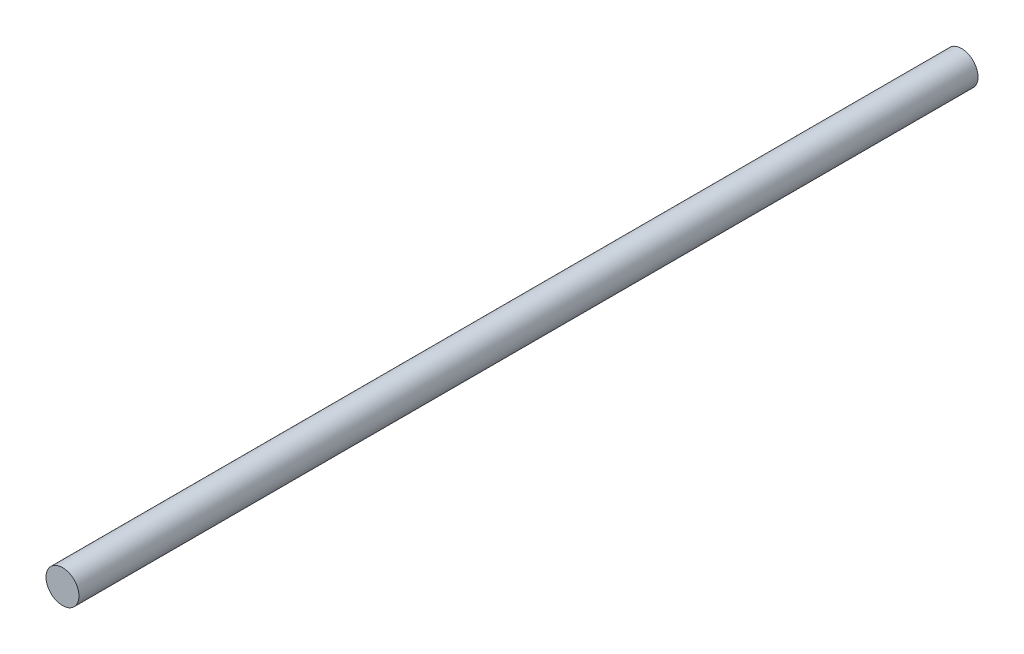
SolidWorks part; units mm, degrees
ref_plane "Plan de face" through (0, 0, 0) normal (0, 0, 1) x (1, 0, 0)
ref_plane "Plan de dessus" through (0, 0, 0) normal (0, 1, 0) x (1, 0, 0)
ref_plane "Plan de droite" through (0, 0, 0) normal (1, 0, 0) x (0, 0, -1)
sketch "Esquisse1" plane through (0, 0, 0) normal (0, 0, 1) x (1, 0, 0)
  circle A0 centre (0, 0) radius 4
  dimension "D1" = 8
extrude "Boss.-Extru.1" add sketch "Esquisse1" along normal blind 218.26
